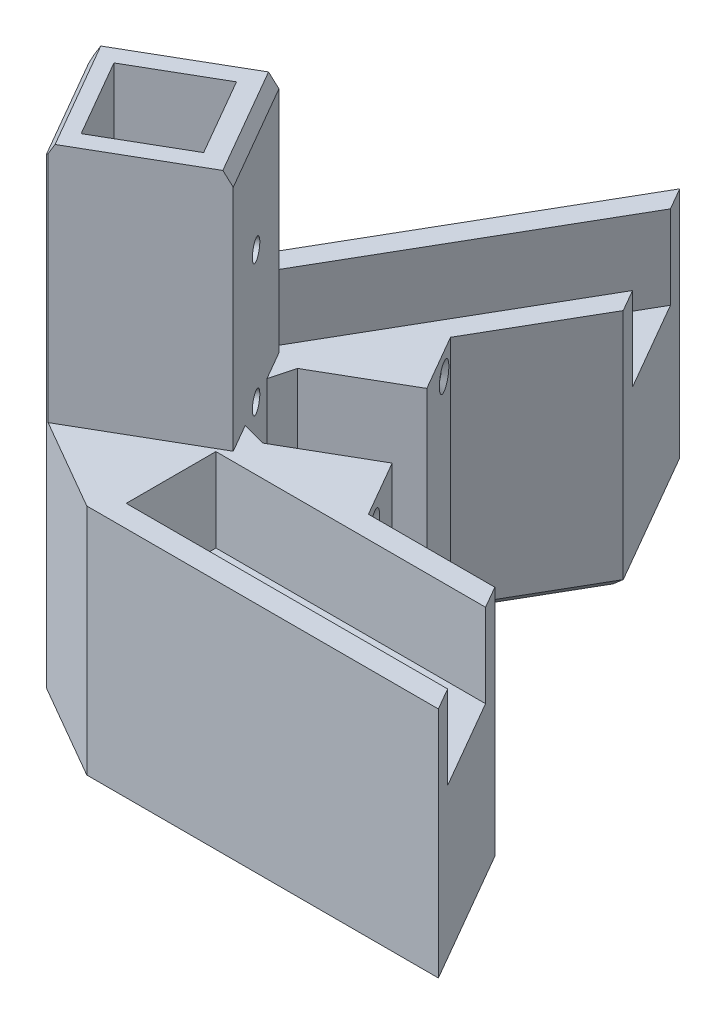
SolidWorks part; units mm, degrees
other "Markup1"
sketch "Sketch26" plane through (25.6218, 0, -129.9038) normal (-0.1134, -0.9932, -0.0259) x (0.9576, -0.1162, 0.2636)
ref_plane "Front Plane" through (0, 0, 0) normal (0, 0, 1) x (1, 0, 0)
ref_plane "Top Plane" through (0, 0, 0) normal (0, 1, 0) x (1, 0, 0)
ref_plane "Right Plane" through (0, 0, 0) normal (1, 0, 0) x (0, 0, -1)
sketch "Sketch1" plane through (0, 0, 0) normal (0, 1, 0) x (1, 0, 0)
  line L0 (0, 0) -> (150, 0)
  line L1 (0, 0) -> (75, 129.9038)
  line L2 (75, 129.9038) -> (150, 0)
  dimension "D1" = 60
  dimension "D2" = 150
  dimension "D3" = 60
sketch "Sketch2" plane through (0, 0, 0) normal (0, 1, 0) x (1, 0, 0)
  line L1 (74.2, 5.2) -> (174.2, 5.2) construction
  line L2 (74.2, 5.2) -> (74.2, 25.2) construction
  line L3 (74.2, 25.2) -> (174.2, 25.2) construction
  line L4 (174.2, 5.2) -> (174.2, 25.2) construction
  line L5 (41.6033, 61.6591) -> (91.6033, 148.2616) construction
  line L6 (91.6033, 148.2616) -> (108.9238, 138.2616) construction
  line L7 (108.9238, 138.2616) -> (58.9238, 51.6591) construction
  line L8 (58.9238, 51.6591) -> (41.6033, 61.6591) construction
  line L9 (0, 0) -> (150, 0) construction
  line L10 (109.197, 138.3348) -> (58.997, 51.3859)
  line L11 (58.997, 51.3859) -> (41.3301, 61.5859)
  line L12 (41.3301, 61.5859) -> (91.5301, 148.5348)
  line L13 (91.5301, 148.5348) -> (109.197, 138.3348)
  line L14 (74, 25.4) -> (174.4, 25.4)
  line L15 (174.4, 5) -> (174.4, 25.4)
  line L16 (74, 5) -> (174.4, 5)
  line L17 (74, 5) -> (74, 25.4)
  line L18 (0, 0) -> (75, 129.9038) construction
  dimension "D1" = 20
  dimension "D2" = 5
  dimension "D3" = 74
  dimension "D4" = 20
  dimension "D5" = 74
  dimension "D6" = 5
  dimension "D7" = 100
  dimension "D8" = 100
  dimension "D9" = 0.2
  dimension "D10" = 0.2
sketch "Sketch4" plane through (0, 0, 0) normal (0, 1, 0) x (1, 0, 0)
  line L4 (0, 0) -> (54.7796, 31.6328) construction
  line L6 (0, 0) -> (53.0061, 91.8093) construction
  line L7 (68.4402, 27.9736) -> (51.1204, 17.9723) construction
  line L8 (68.4402, 27.9736) -> (58.4388, 45.2934) construction
  line L9 (58.4388, 45.2934) -> (41.1191, 35.292) construction
  line L10 (51.1204, 17.9723) -> (41.1191, 35.292) construction
  line L11 (68.4402, 27.9736) -> (41.1191, 35.292) construction
  line L12 (58.4388, 45.2934) -> (51.1204, 17.9723) construction
  line L13 (58.512, 45.5666) -> (40.8459, 35.3652)
  line L15 (0, 0) -> (131.24, 0) construction
  line L17 (51.0473, 17.6991) -> (40.8459, 35.3652)
  line L18 (68.7134, 27.9005) -> (51.0473, 17.6991)
  line L19 (68.7134, 27.9005) -> (58.512, 45.5666)
  point P0 (54.7796, 31.6328)
  dimension "D1" = 20
  dimension "D2" = 20
  dimension "D3" = 30.005
  dimension "D4" = 0.2
  dimension "D5" = 63.2569
  dimension "D6" = 60
ref_plane "Plane1" through (4.3301, 0, 2.5) normal (0.866, 0, 0.5) x (0.5, 0, -0.866)
ref_plane "Plane2" through (21.997, 0, 12.7) normal (-0.866, 0, -0.5) x (-0.5, 0, 0.866)
ref_plane "Plane3" through (0, 0, -25.4) normal (0, 0, 1) x (1, 0, 0)
ref_plane "Plane4" through (0, 0, -5) normal (0, 0, 1) x (1, 0, 0)
ref_plane "Plane6" through (-5.1007, 0, -8.8331) normal (-0.5001, 0, -0.866) x (-0.866, 0, 0.5001)
ref_plane "Plane7" through (5.1007, 0, 8.8331) normal (-0.5001, 0, -0.866) x (-0.866, 0, 0.5001)
extrude "Boss-Extrude1" add sketch "Sketch1" against normal blind 55
extrude "Cut-Extrude2" cut sketch "Sketch4" against normal through all and the other way through all
extrude "Cut-Extrude3" cut sketch "Sketch2" against normal blind 19
sketch "Sketch27" plane through (0, 0, 0) normal (0, 1, 0) x (1, 0, 0)
  line L0 (92.5514, 99.5038) -> (63.4254, 49.0561)
  line L1 (135.3353, 25.4) -> (89.6647, 104.5038) construction
  line L2 (63.4254, 49.0561) -> (74.1985, 30.4)
  line L3 (74.1985, 30.4) -> (132.4486, 30.4)
  line L4 (58.997, 51.3859) -> (89.6647, 104.5038) construction
  line L5 (135.3353, 25.4) -> (74, 25.4) construction
  line L6 (58.512, 45.5666) -> (68.7134, 27.9005) construction
  line L7 (58.997, 51.3859) -> (89.6647, 104.5038) construction
  line L8 (74, 25.4) -> (135.3353, 25.4) construction
  dimension "D1" = 5
  dimension "D2" = 5
  dimension "D3" = 6
extrude "Cut-Extrude4" cut sketch "Sketch27" against normal through all and the other way through all
sketch "Sketch28" plane through (0, 0, 0) normal (0, 1, 0) x (1, 0, 0)
  line L1 (92.5514, 99.5038) -> (63.4254, 49.0561) construction
  line L2 (74.1985, 30.4) -> (132.4486, 30.4) construction
  line L3 (63.4254, 49.0561) -> (74.1985, 30.4) construction
  line L5 (63.4254, 49.0561) -> (78.1721, 74.598)
  line L6 (78.1721, 74.598) -> (85.5454, 61.8294)
  line L7 (103.6944, 30.4) -> (74.1985, 30.4)
  line L8 (85.5454, 61.8294) -> (63.4254, 49.0561)
  line L9 (74.1985, 30.4) -> (96.3184, 43.1733)
  line L10 (96.3184, 43.1733) -> (103.6944, 30.4)
  dimension "D1" = 105
sketch "Sketch36" plane through (0, 0, 0) normal (0, 1, 0) x (1, 0, 0)
  line L0 (0, 0) -> (27.7444, 48.0548)
  line L1 (75, 129.9038) -> (0, 0) construction
  line L2 (27.7444, 48.0548) -> (55.4939, 0)
  line L3 (0, 0) -> (150, 0) construction
  line L4 (55.4939, 0) -> (0, 0)
  line L5 (51.0473, 17.6991) -> (40.8459, 35.3652) construction
  dimension "D1" = 5
extrude "Cut-Extrude12" cut sketch "Sketch36" against normal through all
sketch "Sketch37" plane through (0, 0, 0) normal (0, 1, 0) x (1, 0, 0)
  line L0 (34.5157, 36.3288) -> (61.7076, 52.0309)
  line L3 (55.4939, 0) -> (27.7444, 48.0548) construction
  line L6 (40.8459, 35.3652) -> (58.512, 45.5666) construction
  line L7 (48.7176, 11.7348) -> (75.9096, 27.4369)
  line L9 (68.7134, 27.9005) -> (51.0473, 17.6991) construction
  line L10 (61.7076, 52.0309) -> (75.9096, 27.4369)
  line L14 (58.512, 45.5666) -> (68.7134, 27.9005) construction
  line L15 (34.5157, 36.3288) -> (48.7176, 11.7348)
  line L16 (58.512, 45.5666) -> (40.8459, 35.3652)
  line L17 (40.8459, 35.3652) -> (51.0473, 17.6991)
  line L18 (51.0473, 17.6991) -> (68.7134, 27.9005)
  line L19 (68.7134, 27.9005) -> (58.512, 45.5666)
  dimension "D1" = 4
  dimension "D2" = 4
  dimension "D3" = 6
extrude "Boss-Extrude2" add sketch "Sketch37" along normal blind 55
chamfer "Chamfer1" distance 14.54 angle 30 1 edges at (27.7444, -27.5, -48.0548)
chamfer "Chamfer8" distance 14.54 angle 30 1 edges at (55.4939, -27.5, 0)
chamfer "Chamfer10" distance 3 angle 30 2 edges at (41.6187, 55, -24.0282) (68.8086, 55, -39.7339)
extrude "Boss-Extrude4" add sketch "Sketch28" against normal up to surface (55 mm away) up to face at (77.5909, -55, -44.7965)
sketch "Sketch39" plane through (90.9285, 0, -52.5072) normal (0.866, 0, -0.5001) x (-0.5001, 0, -0.866)
  line L0 (-25.5284, 0) -> (-10.7784, 0) construction
  line L1 (-21.5, -48) -> (21.5, -48) construction
  line L2 (-21.5, -48) -> (-21.5, -5) construction
  line L3 (-21.5, -5) -> (21.5, -5) construction
  line L4 (21.5, -48) -> (21.5, -5) construction
  line L5 (-21.5, -48) -> (21.5, -5) construction
  line L6 (-21.5, -5) -> (21.5, -48) construction
  circle A0 centre (-21.5, -5) radius 1.95
  circle A1 centre (21.5, -5) radius 1.95
  circle A2 centre (21.5, -48) radius 1.95
  circle A3 centre (-21.5, -48) radius 1.95
  point P0 (0, -26.5)
  dimension "D4" = 3.9
  dimension "D1" = 43
  dimension "D2" = 43
  dimension "D3" = 5
extrude "Cut-Extrude13" cut sketch "Sketch39" against normal blind 11
sketch "Sketch40" plane through (0, -19, 0) normal (0, 1, 0) x (1, 0, 0)
  line L0 (50.1636, 56.4859) -> (83.7757, 114.7038) construction
  line L1 (41.3301, 61.5859) -> (58.997, 51.3859) construction
  line L2 (89.6647, 104.5038) -> (77.8868, 124.9038) construction
  circle A0 centre (76.2757, 101.7134) radius 2.3
  circle A1 centre (57.6636, 69.4763) radius 2.3
  dimension "D1" = 4.6
  dimension "D2" = 15
  dimension "D3" = 15
extrude "Cut-Extrude14" cut sketch "Sketch40" against normal through all
sketch "Sketch41" plane through (0, -19, 0) normal (0, 1, 0) x (1, 0, 0)
  line L0 (74, 15.2) -> (141.2243, 15.2) construction
  line L1 (74, 25.4) -> (74, 5) construction
  line L2 (147.1132, 5) -> (135.3353, 25.4) construction
  circle A0 centre (89, 15.2) radius 2.3
  circle A1 centre (126.2243, 15.2) radius 2.3
  dimension "D1" = 4.6
  dimension "D2" = 15
  dimension "D3" = 15
extrude "Cut-Extrude15" cut sketch "Sketch41" against normal through all
ref_plane "Plane8" through (0, -24, 0) normal (0, 1, 0) x (1, 0, 0)
sketch "Sketch42" plane through (0, -24, 0) normal (0, 1, 0) x (1, 0, 0)
  circle A0 centre (76.2757, 101.7134) radius 5
  circle A1 centre (57.6636, 69.4763) radius 5
  circle A2 centre (89, 15.2) radius 5
  circle A3 centre (126.2243, 15.2) radius 5
  dimension "D1" = 10
extrude "Cut-Extrude16" cut sketch "Sketch42" against normal through all
chamfer "Chamfer6" distance 1 angle 45 4 edges at (49.6789, -55, -40.4659) (45.9466, -55, -26.5321) (59.8803, -55, -22.7998) (63.6127, -55, -36.7335)
chamfer "Chamfer13" distance 2 angle 45 4 edges at (126.2243, -55, -10.2) (89, -55, -10.2) (76.2757, -55, -96.7134) (57.6636, -55, -64.4763)
chamfer "Chamfer14" distance 4 angle 45 2 edges at (63.4254, -27.5, -49.0561) (74.1985, -27.5, -30.4)
sketch "Sketch35" plane through (45.9466, 0, -26.5321) normal (0.866, 0, -0.5001) x (-0.5001, 0, -0.866)
  line L0 (0, 0) -> (0, -55) construction
  circle A0 centre (0, -30) radius 2.3
  circle A1 centre (0, 0) radius 2.3
  circle A2 centre (0, 30) radius 2.3
  dimension "D3" = 4.6
  dimension "D1" = 30
  dimension "D4" = 30
extrude "Cut-Extrude11" cut sketch "Sketch35" along normal through all
chamfer "Chamfer15" distance 1 angle 45 4 edges at (79.2019, -48, -72.8146) (100.7048, -48, -35.5772) (100.7048, -5, -35.5772) (79.2019, -5, -72.8146)
chamfer "Chamfer12" distance 2 angle 45 16 edges at (86.9905, -55, -37.7868) (100.0064, -55, -36.7866) (118.0715, -55, -30.4) (141.2243, -55, -15.2) (110.017, -55, 0) (59.1279, -55, -6.2966) (41.6187, -55, -24.0282) (35.0144, -55, -48.0542) (55.0067, -55, -95.2744) (83.7757, -55, -114.7038) (85.3618, -55, -87.0509) (81.8587, -55, -68.2137) (76.2174, -55, -56.4429) (68.812, -55, -39.728) (66.1576, -55, -48.3243) (74.9304, -55, -33.1321)
